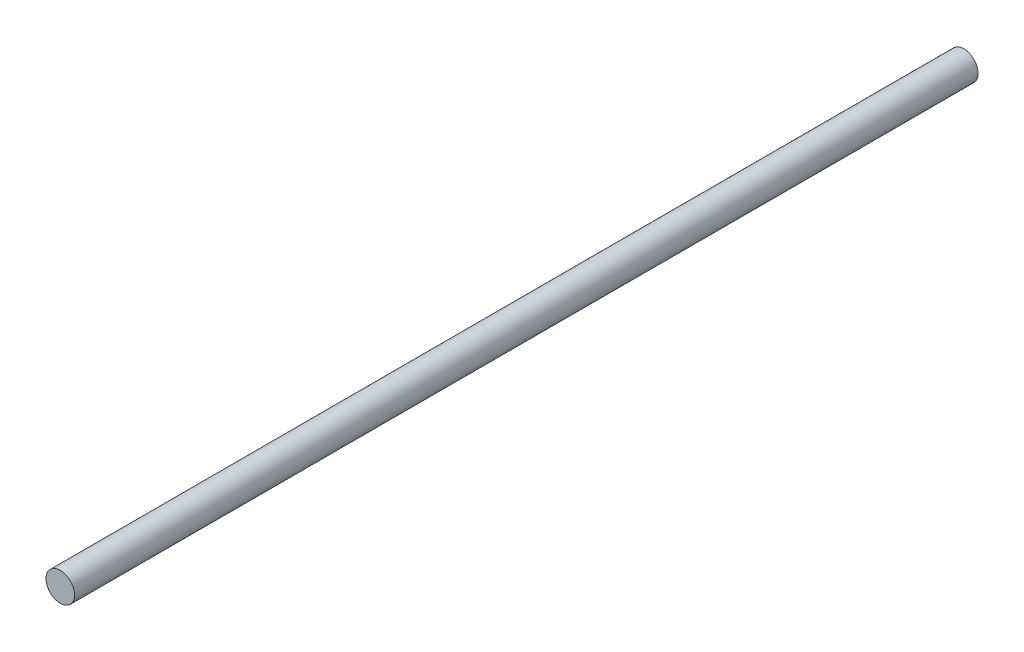
SolidWorks part; units mm, degrees
ref_plane "Front Plane" through (0, 0, 0) normal (0, 0, 1) x (1, 0, 0)
ref_plane "Top Plane" through (0, 0, 0) normal (0, 1, 0) x (1, 0, 0)
ref_plane "Right Plane" through (0, 0, 0) normal (1, 0, 0) x (0, 0, -1)
sketch "Sketch1" plane through (0, 0, 0) normal (0, 0, 1) x (1, 0, 0)
  circle A0 centre (0, 0) radius 3.81
  dimension "D1" = 7.62
extrude "Boss-Extrude1" add sketch "Sketch1" along normal blind 241.3 contours A0
